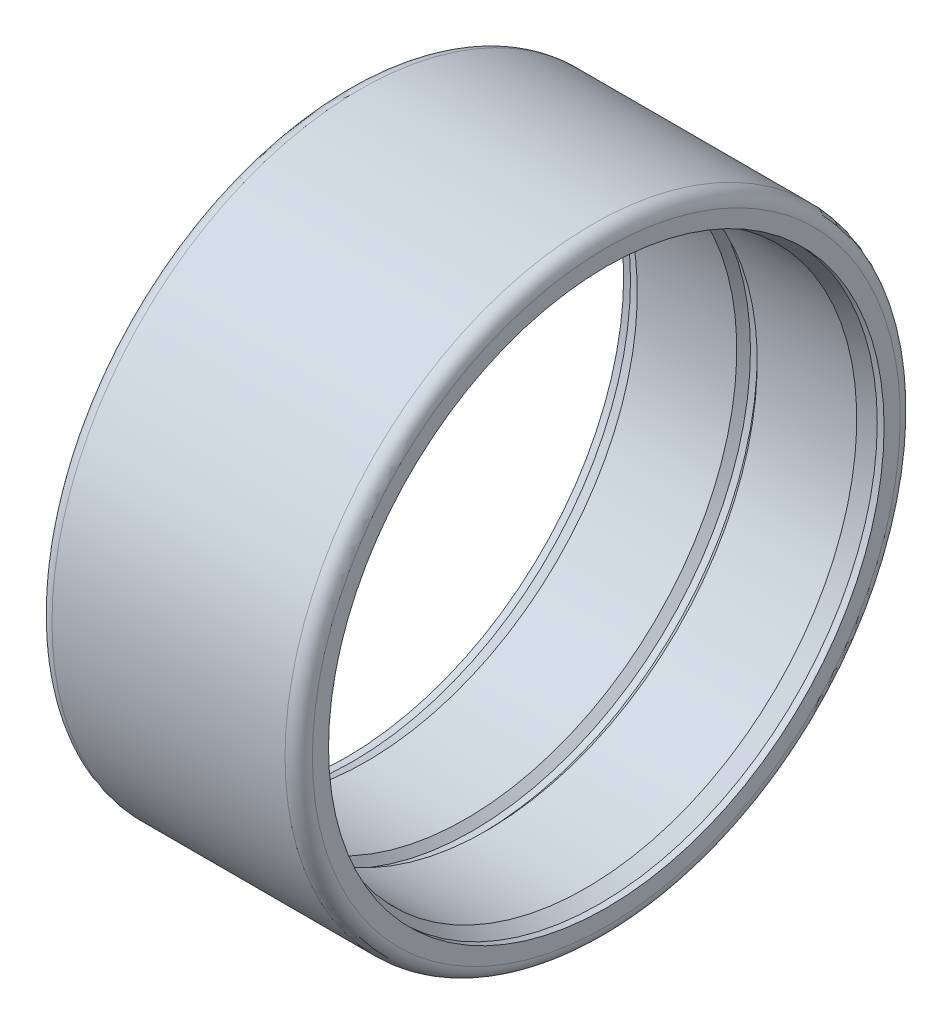
SolidWorks part; units mm, degrees
material "BUTYL"
ref_plane "Front Plane" through (0, 0, 0) normal (0, 0, 1) x (1, 0, 0)
ref_plane "Top Plane" through (0, 0, 0) normal (0, 1, 0) x (1, 0, 0)
ref_plane "Right Plane" through (0, 0, 0) normal (1, 0, 0) x (0, 0, -1)
sketch "Sketch1" plane through (0, 0, 0) normal (0, 0, 1) x (1, 0, 0)
  line L0 (-32.3713, 0) -> (29.234, 0) construction
  line L1 (-7.5, 198.2) -> (-80.25, 198.2)
  line L2 (-80.25, 198.2) -> (-90.25, 203.2)
  line L3 (-90.25, 203.2) -> (-95.25, 203.2)
  line L4 (80.25, 198.2) -> (90.25, 203.2)
  line L5 (80.25, 198.2) -> (7.5, 198.2)
  line L6 (-2.5, 203.2) -> (2.5, 203.2)
  line L7 (2.5, 203.2) -> (7.5, 198.2)
  line L8 (-2.5, 203.2) -> (-7.5, 198.2)
  line L9 (90.25, 203.2) -> (95.25, 203.2)
  line L10 (0, -14.5563) -> (0, 275.5167) construction
  line L11 (-95.25, 203.2) -> (-95.25, 225)
  line L12 (95.25, 203.2) -> (95.25, 225)
  line L13 (95.25, 225) -> (-95.25, 225)
  point P11 (0, 203.2)
  dimension "D1" = 5
  dimension "D2" = 406.4
  dimension "D3" = 5
  dimension "D4" = 10
  dimension "D5" = 190.5
  dimension "D6" = 5
  dimension "D7" = 450
revolve "Revolve1" add sketch "Sketch1" angle 360 about L0
fillet "Fillet1" radius 10 2 edges at (95.25, 0, 225) (-95.25, 0, 225)
